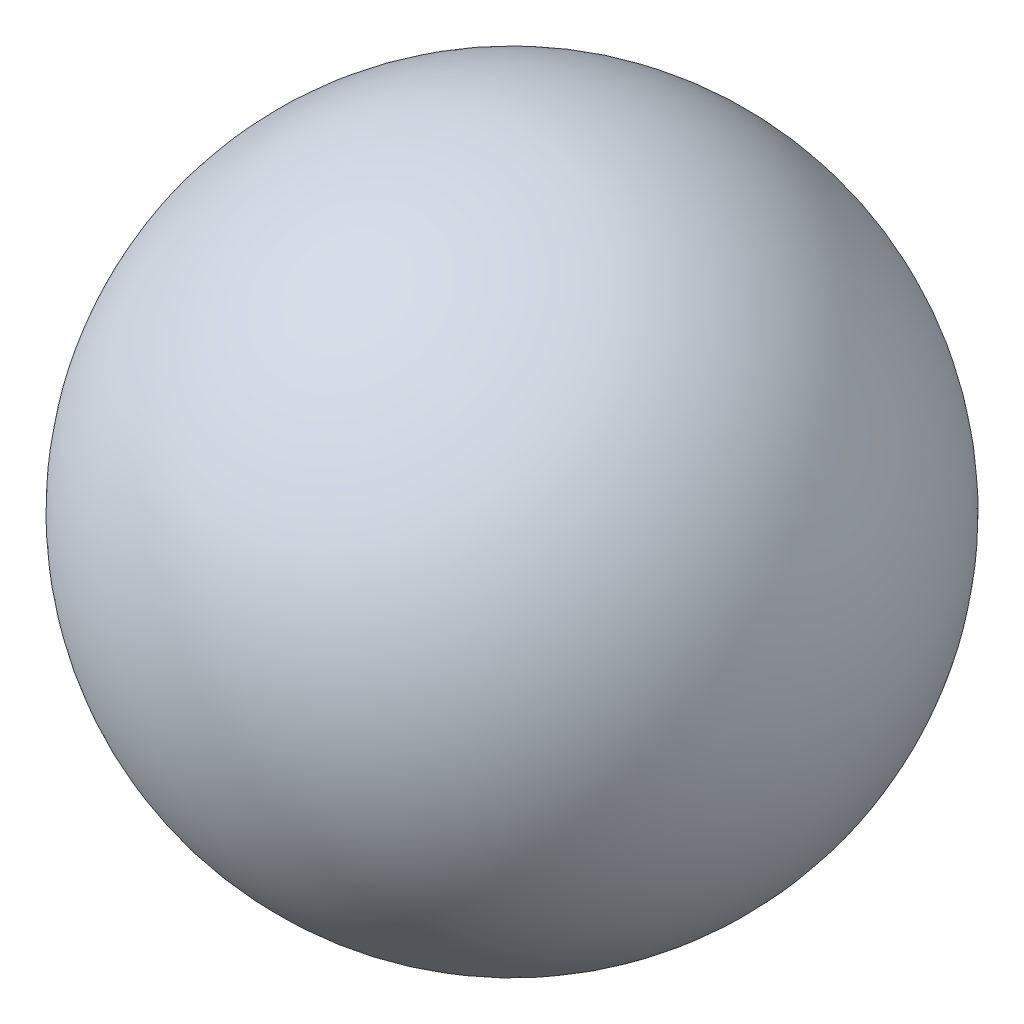
SolidWorks part; units mm, degrees
ref_plane "Alzado" through (0, 0, 0) normal (0, 0, 1) x (1, 0, 0)
ref_plane "Planta" through (0, 0, 0) normal (0, 1, 0) x (1, 0, 0)
ref_plane "Vista lateral" through (0, 0, 0) normal (1, 0, 0) x (0, 0, -1)
sketch "Croquis1" plane through (0, 0, 0) normal (0, 1, 0) x (1, 0, 0)
  line L0 (-8, 0) -> (12, 0) construction
  line L2 (8, 0) -> (-8, 0)
  arc A0 (8, 0) -> (-8, 0) centre (0, 0) ccw
  dimension "D1" = 16
revolve "Revolución4" add sketch "Croquis1" angle 360 about L0
